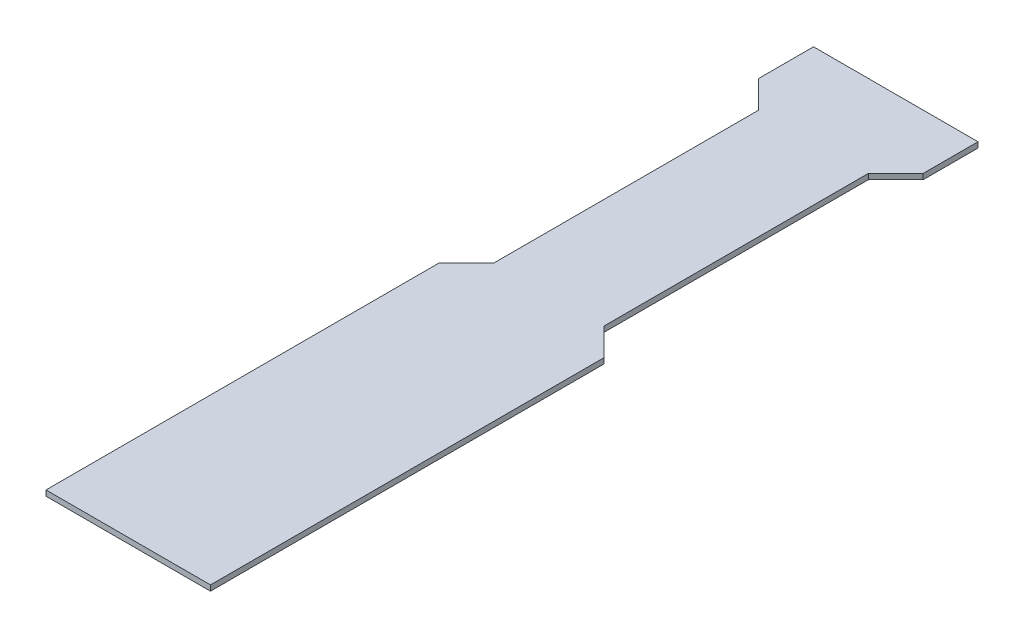
SolidWorks part; units mm, degrees
ref_plane "前视基准面" through (0, 0, 0) normal (0, 0, 1) x (1, 0, 0)
ref_plane "上视基准面" through (0, 0, 0) normal (0, 1, 0) x (1, 0, 0)
ref_plane "右视基准面" through (0, 0, 0) normal (1, 0, 0) x (0, 0, -1)
sketch "草图1" plane through (0, 0, 0) normal (0, 1, 0) x (1, 0, 0)
  line L26 (30, 260) -> (30, 280)
  line L33 (30, 143.5) -> (20, 153.5)
  line L34 (20, 240) -> (20, 153.5)
  line L35 (30, 260) -> (20, 250)
  line L36 (20, 250) -> (20, 240)
  line L37 (-30, 280) -> (30, 280)
  line L38 (-20, 250) -> (-20, 240)
  line L39 (-30, 260) -> (-20, 250)
  line L40 (-20, 240) -> (-20, 153.5)
  line L41 (-30, 143.5) -> (-20, 153.5)
  line L42 (-30, 260) -> (-30, 280)
  line L43 (30, 143.5) -> (30, 0)
  line L44 (30, 0) -> (0, 0)
  line L45 (0, 0) -> (-30, 0)
  line L46 (-30, 0) -> (-30, 143.5)
  point P27 (0, 320)
extrude "凸台-拉伸1" add sketch "草图1" along normal blind 2
